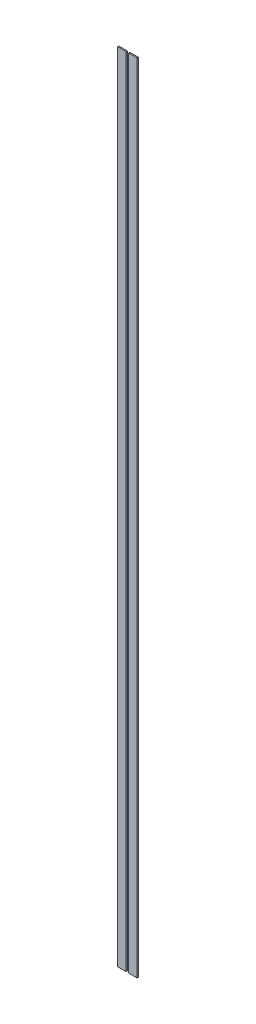
SolidWorks part; units mm, degrees
ref_plane "Plan de face" through (0, 0, 0) normal (0, 0, 1) x (1, 0, 0)
ref_plane "Plan de dessus" through (0, 0, 0) normal (0, 1, 0) x (1, 0, 0)
ref_plane "Plan de droite" through (0, 0, 0) normal (1, 0, 0) x (0, 0, -1)
sketch "Esquisse1" plane through (0, 0, 0) normal (0, 0, 1) x (1, 0, 0)
  line L0 (0, 0) -> (0, 96.3982) construction
  line L1 (8, 380) -> (8, -280)
  line L2 (-8, 380) -> (-1, 380)
  line L3 (-8, 380) -> (-8, -280)
  line L4 (-8, -280) -> (-1, -280)
  line L5 (-1, 380) -> (-1, -280)
  line L6 (8, 380) -> (1, 380)
  line L7 (1, 380) -> (1, -280)
  line L8 (8, -280) -> (1, -280)
  dimension "D1" = 660
  dimension "D2" = 280
  dimension "D3" = 7
  dimension "D4" = 2
extrude "Extrusion1" add sketch "Esquisse1" along normal blind 1
